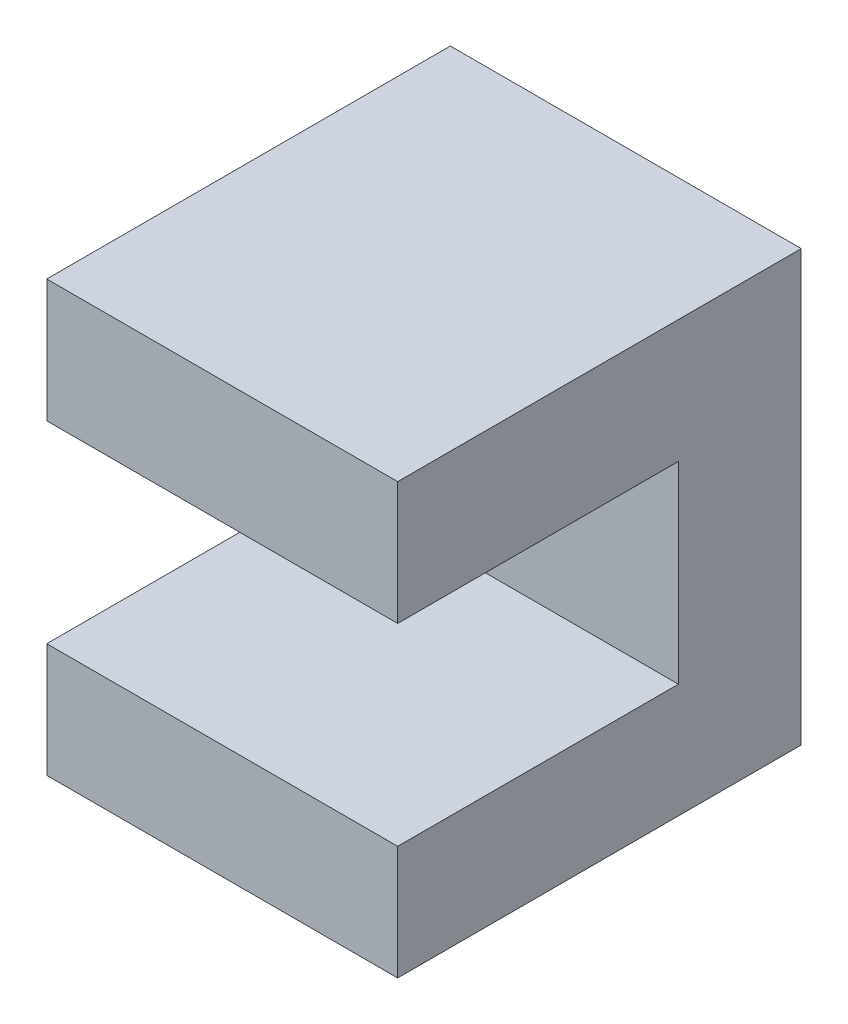
SolidWorks part; units mm, degrees
ref_plane "Front Plane" through (0, 0, 0) normal (0, 0, 1) x (1, 0, 0)
ref_plane "Top Plane" through (0, 0, 0) normal (0, 1, 0) x (1, 0, 0)
ref_plane "Right Plane" through (0, 0, 0) normal (1, 0, 0) x (0, 0, -1)
sketch "Sketch1" plane through (0, 0, 0) normal (1, 0, 0) x (0, 0, -1)
  line L1 (0, 0) -> (-23, 0)
  line L2 (0, 0) -> (0, 6.5)
  line L3 (0, 6.5) -> (-23, 6.5)
  line L4 (-23, 0) -> (-23, 6.5)
  line L5 (0, 6.5) -> (-7, 6.5)
  line L6 (0, 6.5) -> (0, 17.5)
  line L7 (0, 17.5) -> (-7, 17.5)
  line L8 (-7, 6.5) -> (-7, 17.5)
  line L9 (0, 17.5) -> (-23, 17.5)
  line L10 (0, 17.5) -> (0, 24.5)
  line L11 (0, 24.5) -> (-23, 24.5)
  line L12 (-23, 17.5) -> (-23, 24.5)
  line L17 (-23, 24.5) -> (-53.2566, 24.5)
  line L18 (-23, 24.5) -> (-23, 19.5)
  line L19 (-23, 19.5) -> (-53.2566, 19.5)
  line L20 (-53.2566, 24.5) -> (-53.2566, 19.5)
  dimension "D1" = 6.5
  dimension "D2" = 11
  dimension "D3" = 7
  dimension "D4" = 7
  dimension "D5" = 23
  dimension "D6" = 23
  dimension "D7" = 5
extrude "Boss-Extrude1" add sketch "Sketch1" along normal blind 20 contours L8 L3 L6 L7 | L12 L9 L7 L10 L11 | L4 L1 L2 L3
